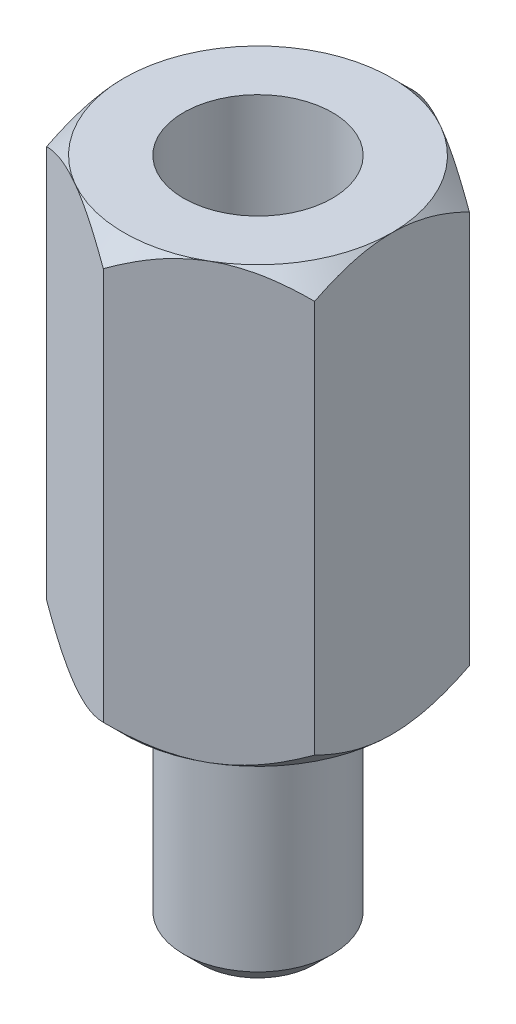
SolidWorks part; units mm, degrees
ref_plane "Front Plane" through (0, 0, 0) normal (0, 0, 1) x (1, 0, 0)
ref_plane "Top Plane" through (0, 0, 0) normal (0, 1, 0) x (1, 0, 0)
ref_plane "Right Plane" through (0, 0, 0) normal (1, 0, 0) x (0, 0, -1)
sketch "Sketch1" plane through (0, 0, 0) normal (0, 1, 0) x (1, 0, 0)
  line L1 (2.2517, 1.3) -> (0, 2.6)
  line L2 (0, 2.6) -> (-2.2517, 1.3)
  line L3 (-2.2517, 1.3) -> (-2.2517, -1.3)
  line L4 (-2.2517, -1.3) -> (0, -2.6)
  line L5 (0, -2.6) -> (2.2517, -1.3)
  line L6 (2.2517, -1.3) -> (2.2517, 1.3)
  circle A0 centre (0, 0) radius 2.2517 construction
  dimension "D1" = 2.6
extrude "Boss-Extrude1" add sketch "Sketch1" against normal blind 7.3
sketch "Sketch2" plane through (0, 0, 0) normal (0, 1, 0) x (1, 0, 0)
  circle A0 centre (0, 0) radius 2.2517
  circle A1 centre (0, 0) radius 1.25
  dimension "D1" = 2.5
sketch "Sketch5" plane through (0, -7.3, 0) normal (0, -1, 0) x (1, 0, 0)
  circle A0 centre (0, 0) radius 1.25 construction
  circle A1 centre (0, 0) radius 1.25
extrude "Boss-Extrude2" add sketch "Sketch5" along normal blind 4
extrude "Cut-Extrude3" cut sketch "Sketch2" against normal up to surface (7.3 mm away) contours A1 up to face at (0, -7.3, -1.25)
sketch "Sketch6" plane through (0, -7.3, 0) normal (0, -1, 0) x (1, 0, 0)
  line L0 (-2.2517, 1.3) -> (0, 2.6) construction
  circle A0 centre (0, 0) radius 2.2517
  circle A1 centre (0, 0) radius 3.326
sketch "Sketch7" plane through (0, 0, 0) normal (0, 1, 0) x (1, 0, 0)
  circle A0 centre (0, 0) radius 3.326 construction
  circle A1 centre (0, 0) radius 3.326
  circle A2 centre (0, 0) radius 2.2517 construction
  circle A3 centre (0, 0) radius 2.2517
extrude "Cut-Extrude7" cut sketch "Sketch7" against normal through all draft 45
extrude "Cut-Extrude8" cut sketch "Sketch6" against normal through all draft 45
sketch "Sketch8" plane through (0, -11.3, 0) normal (0, -1, 0) x (1, 0, 0)
  circle A0 centre (0, 0) radius 0.95
  circle A1 centre (0, 0) radius 1.7912
  dimension "D1" = 1.9
extrude "Cut-Extrude12" cut sketch "Sketch8" against normal through all draft 45
